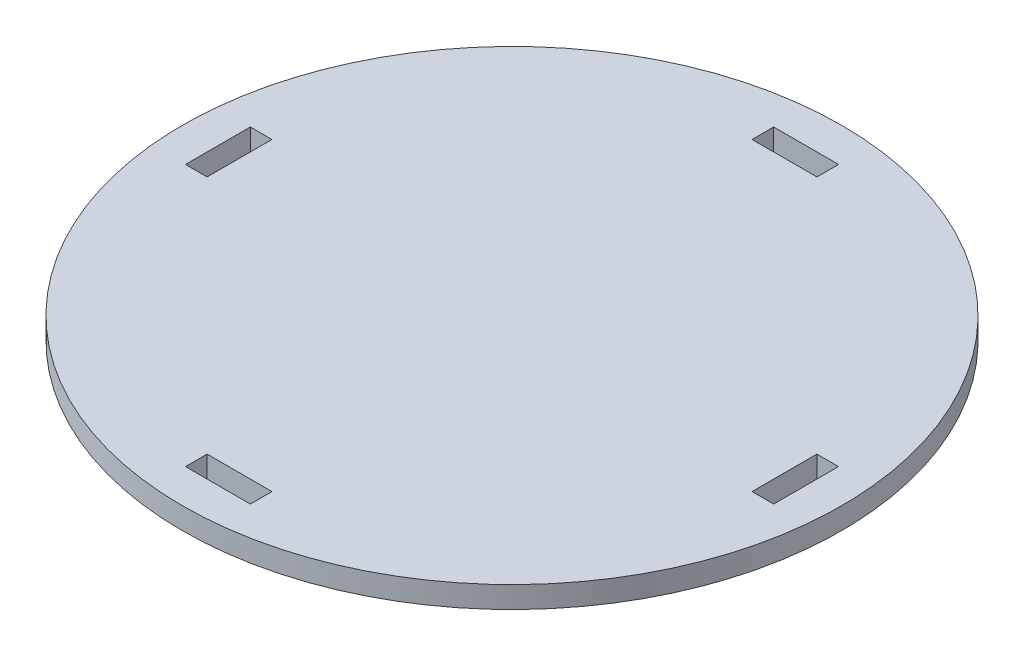
SolidWorks part; units mm, degrees
ref_plane "Front Plane" through (0, 0, 0) normal (0, 0, 1) x (1, 0, 0)
ref_plane "Top Plane" through (0, 0, 0) normal (0, 1, 0) x (1, 0, 0)
ref_plane "Right Plane" through (0, 0, 0) normal (1, 0, 0) x (0, 0, -1)
sketch "Sketch1" plane through (0, 0, 0) normal (0, 1, 0) x (1, 0, 0)
  line L0 (0, 0) -> (122.8247, 0) construction
  line L1 (122.8247, 0) -> (-116.4607, 0) construction
  line L2 (0, -96.9142) -> (0, 92.5503) construction
  line L3 (7.5, 68) -> (-7.5, 68)
  line L4 (-63, 7.5) -> (-68, 7.5)
  line L5 (-63, 7.5) -> (-63, -7.5)
  line L6 (-63, -7.5) -> (-68, -7.5)
  line L7 (-68, 7.5) -> (-68, -7.5)
  line L8 (7.5, 63) -> (7.5, 68)
  line L9 (7.5, 63) -> (-7.5, 63)
  line L10 (-7.5, 63) -> (-7.5, 68)
  line L11 (68, -7.5) -> (68, 7.5)
  line L12 (63, -7.5) -> (68, -7.5)
  line L13 (63, -7.5) -> (63, 7.5)
  line L14 (63, 7.5) -> (68, 7.5)
  line L15 (-7.5, -68) -> (7.5, -68)
  line L16 (-7.5, -63) -> (-7.5, -68)
  line L17 (-7.5, -63) -> (7.5, -63)
  line L18 (7.5, -63) -> (7.5, -68)
  circle A0 centre (0, 0) radius 76.2
  circle A1 centre (0, 0) radius 72 construction
  point P12 (-65.5, 7.5)
  point P28 (0, 0)
  dimension "D1" = 152.4
  dimension "D2" = 144
  dimension "D3" = 15
  dimension "D4" = 5
  dimension "D5" = 7.5
  dimension "D6" = 63
  dimension "D7" = 4
extrude "Boss-Extrude1" add sketch "Sketch1" along normal blind 5
